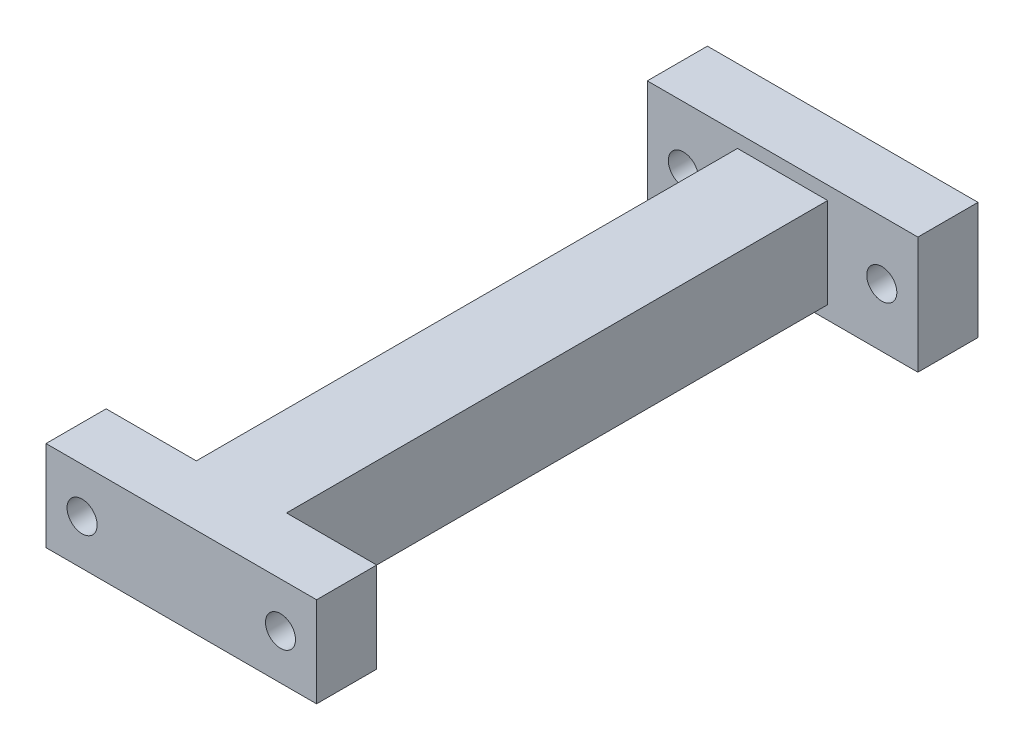
SolidWorks part; units mm, degrees
ref_plane "前视基准面" through (0, 0, 0) normal (0, 0, 1) x (1, 0, 0)
ref_plane "上视基准面" through (0, 0, 0) normal (0, 1, 0) x (1, 0, 0)
ref_plane "右视基准面" through (0, 0, 0) normal (1, 0, 0) x (0, 0, -1)
sketch "草图1" plane through (0, 0, 0) normal (0, 0, 1) x (1, 0, 0)
  line L1 (7.5, -7.5) -> (-7.5, -7.5)
  line L2 (7.5, -7.5) -> (7.5, 7.5)
  line L3 (7.5, 7.5) -> (-7.5, 7.5)
  line L4 (-7.5, -7.5) -> (-7.5, 7.5)
  line L5 (7.5, -7.5) -> (-7.5, 7.5) construction
  line L6 (7.5, 7.5) -> (-7.5, -7.5) construction
  point P0 (0, 0)
  dimension "D1" = 15
  dimension "D2" = 15
extrude "凸台-拉伸1" add sketch "草图1" along normal blind 110
sketch "草图2" plane through (0, 0, 110) normal (0, 0, 1) x (1, 0, 0)
  line L1 (22.5, -7.5) -> (-22.5, -7.5)
  line L2 (22.5, -7.5) -> (22.5, 7.5)
  line L3 (22.5, 7.5) -> (-22.5, 7.5)
  line L4 (-22.5, -7.5) -> (-22.5, 7.5)
  line L5 (22.5, -7.5) -> (-22.5, 7.5) construction
  line L6 (22.5, 7.5) -> (-22.5, -7.5) construction
  point P0 (0, 0)
  dimension "D1" = 15
  dimension "D2" = 45
extrude "凸台-拉伸2" add sketch "草图2" against normal blind 10
sketch "草图3" plane through (0, 0, 110) normal (0, 0, 1) x (1, 0, 0)
  line L0 (-22.5, 7.5) -> (-22.5, -7.5) construction
  line L2 (0, -8.25) -> (0, 8.25) construction
  circle A0 centre (-16.5, 0) radius 2.5
  circle A1 centre (16.5, 0) radius 2.5
  dimension "D1" = 6
  dimension "D2" = 5
extrude "切除-拉伸1" cut sketch "草图3" against normal blind 20
sketch "草图5" plane through (0, 0, 0) normal (0, 0, -1) x (-1, 0, 0)
  line L1 (22.5, -9.7364) -> (-22.5, -9.7364)
  line L2 (22.5, -9.7364) -> (22.5, 9.7364)
  line L3 (22.5, 9.7364) -> (-22.5, 9.7364)
  line L4 (-22.5, -9.7364) -> (-22.5, 9.7364)
  line L5 (22.5, -9.7364) -> (-22.5, 9.7364) construction
  line L6 (22.5, 9.7364) -> (-22.5, -9.7364) construction
  point P0 (0, 0)
  dimension "D1" = 45
extrude "凸台-拉伸3" add sketch "草图5" against normal blind 10
sketch "草图6" plane through (0, 0, 0) normal (0, 0, -1) x (-1, 0, 0)
  line L0 (-22.5, 9.7364) -> (-22.5, -9.7364) construction
  line L1 (22.5, -9.7364) -> (22.5, 9.7364) construction
  circle A0 centre (-16.5, 0) radius 2.5
  circle A1 centre (16.5, 0) radius 2.5
  point P6 (-22.5, 0)
  point P9 (22.5, 0)
  dimension "D1" = 6
  dimension "D3" = 5
  dimension "D4" = 5
  dimension "D2" = 6
extrude "切除-拉伸2" cut sketch "草图6" against normal through all
